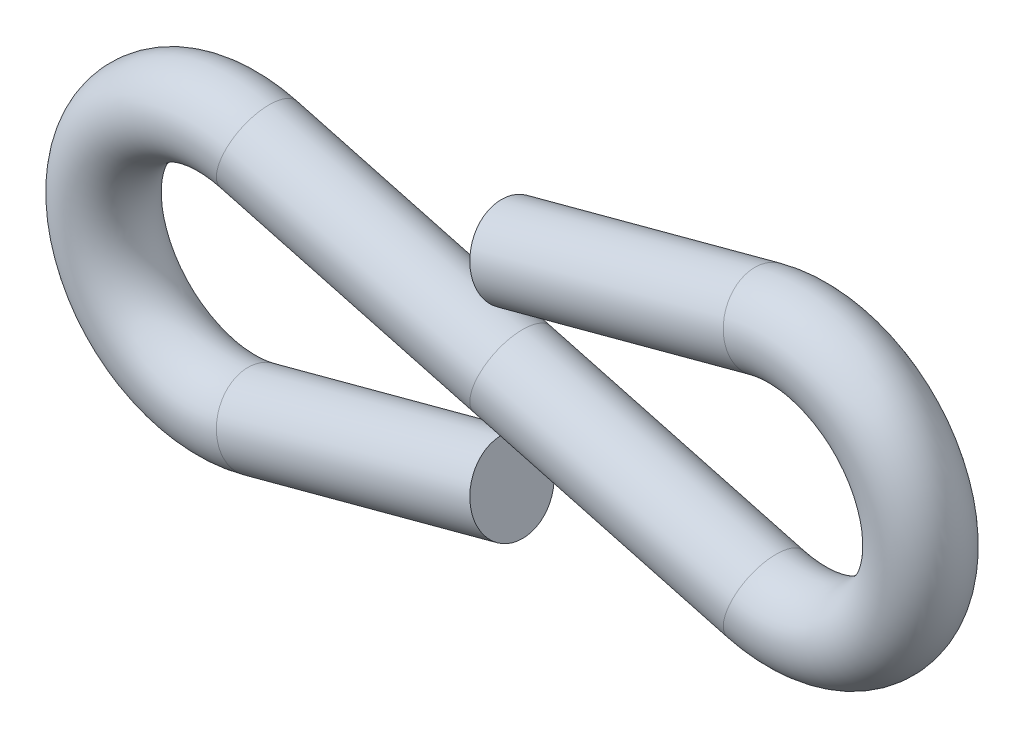
SolidWorks part; units mm, degrees
ref_plane "Спереди" through (0, 0, 0) normal (0, 0, 1) x (1, 0, 0)
ref_plane "Сверху" through (0, 0, 0) normal (0, 1, 0) x (1, 0, 0)
ref_plane "Справа" through (0, 0, 0) normal (1, 0, 0) x (0, 0, -1)
sketch "Эскиз1" plane through (0, 0, 0) normal (0, 0, 1) x (1, 0, 0)
  line L0 (0, 0) -> (18.6132, -4.9874)
  line L1 (18.6132, 12.4874) -> (0, 7.5)
  line L5 (-18.6132, -12.4874) -> (0, -7.5)
  line L6 (0, 0) -> (-18.6132, 4.9874)
  arc A0 (18.6132, -4.9874) -> (18.6132, 12.4874) centre (20.9544, 3.75) ccw
  arc A1 (-18.6132, 4.9874) -> (-18.6132, -12.4874) centre (-20.9544, -3.75) ccw
  point P13 (0, 0)
  dimension "D1" = 60
  dimension "D2" = 7.5
  dimension "D3" = 2
  dimension "D4" = 30
  dimension "D5" = 3.75
sweep "По траектории1" add path "Эскиз1" circular profile diameter 6 parameters "D3"=6
